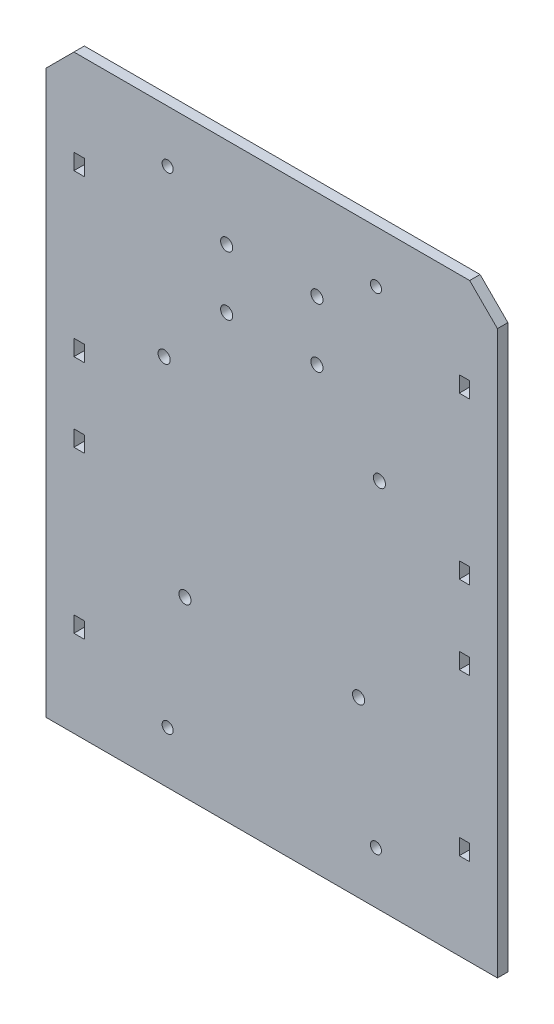
SolidWorks part; units mm, degrees
ref_plane "正面" through (0, 0, 0) normal (0, 0, 1) x (1, 0, 0)
ref_plane "平面" through (0, 0, 0) normal (0, 1, 0) x (1, 0, 0)
ref_plane "右側面" through (0, 0, 0) normal (1, 0, 0) x (0, 0, -1)
sketch "ｽｹｯﾁ1" plane through (0, 0, 0) normal (0, 0, 1) x (1, 0, 0)
  line L0 (0, 162) -> (8, 170)
  line L1 (0, 0) -> (130, 0)
  line L2 (0, 0) -> (0, 162)
  line L3 (8, 170) -> (122, 170)
  line L4 (130, 0) -> (130, 162)
  line L5 (8, 145) -> (11, 145)
  line L6 (8, 145) -> (8, 140.4)
  line L7 (8, 140.4) -> (11, 140.4)
  line L8 (11, 145) -> (11, 140.4)
  line L9 (122, 145) -> (119, 145)
  line L10 (122, 145) -> (122, 140.4)
  line L11 (122, 140.4) -> (119, 140.4)
  line L12 (119, 145) -> (119, 140.4)
  line L13 (8, 29.6) -> (11, 29.6)
  line L14 (8, 29.6) -> (8, 25)
  line L15 (8, 25) -> (11, 25)
  line L16 (11, 29.6) -> (11, 25)
  line L17 (119, 29.6) -> (122, 29.6)
  line L18 (119, 29.6) -> (119, 25)
  line L19 (119, 25) -> (122, 25)
  line L20 (122, 29.6) -> (122, 25)
  line L21 (8, 98.6) -> (11, 98.6)
  line L22 (8, 98.6) -> (8, 94)
  line L23 (8, 94) -> (11, 94)
  line L24 (11, 98.6) -> (11, 94)
  line L25 (119, 98.6) -> (122, 98.6)
  line L26 (119, 98.6) -> (119, 94)
  line L27 (119, 94) -> (122, 94)
  line L28 (122, 98.6) -> (122, 94)
  line L29 (8, 76) -> (11, 76)
  line L30 (8, 76) -> (8, 71.4)
  line L31 (8, 71.4) -> (11, 71.4)
  line L32 (11, 76) -> (11, 71.4)
  line L33 (119, 76) -> (122, 76)
  line L34 (119, 76) -> (119, 71.4)
  line L35 (119, 71.4) -> (122, 71.4)
  line L36 (122, 76) -> (122, 71.4)
  line L37 (122, 170) -> (130, 162)
  circle A0 centre (35, 155) radius 1.6
  circle A1 centre (95, 155) radius 1.6
  circle A2 centre (35, 15) radius 1.6
  circle A3 centre (95, 15) radius 1.6
  circle A4 centre (34, 107) radius 1.75
  circle A5 centre (96, 107) radius 1.75
  circle A6 centre (40, 50) radius 1.75
  circle A7 centre (90, 50) radius 1.75
  circle A8 centre (52, 144) radius 1.75
  circle A9 centre (78, 144) radius 1.75
  circle A10 centre (52, 127) radius 1.75
  circle A11 centre (78, 127) radius 1.75
  point P21 (119, 142.7)
  point P38 (8, 27.3)
  point P39 (9.5, 25)
  point P66 (0, 0)
  dimension "D40" = 3.2
  dimension "D41" = 3.2
  dimension "D42" = 3.2
  dimension "D43" = 3.2
  dimension "D52" = 3.5
  dimension "D53" = 3.5
  dimension "D54" = 3.5
  dimension "D55" = 3.5
  dimension "D64" = 3.5
  dimension "D65" = 3.5
  dimension "D66" = 3.5
  dimension "D67" = 3.5
  dimension "D1" = 170
  dimension "D3" = 3
  dimension "D4" = 4.6
  dimension "D5" = 3
  dimension "D6" = 4.6
  dimension "D7" = 3
  dimension "D8" = 4.6
  dimension "D9" = 3
  dimension "D10" = 4.6
  dimension "D11" = 3
  dimension "D12" = 4.6
  dimension "D13" = 3
  dimension "D14" = 4.6
  dimension "D15" = 4.6
  dimension "D16" = 3
  dimension "D17" = 3
  dimension "D18" = 4.6
  dimension "D19" = 51
  dimension "D20" = 51
  dimension "D21" = 8
  dimension "D22" = 8
  dimension "D23" = 8
  dimension "D24" = 8
  dimension "D25" = 8
  dimension "D26" = 8
  dimension "D27" = 51
  dimension "D28" = 51
  dimension "D29" = 8
  dimension "D30" = 8
  dimension "D31" = 25
  dimension "D32" = 25
  dimension "D33" = 25
  dimension "D34" = 25
  dimension "D35" = 130
  dimension "D36" = 8
  dimension "D37" = 11.3137
  dimension "D38" = 11.3137
  dimension "D39" = 45
  dimension "D44" = 35
  dimension "D45" = 35
  dimension "D46" = 35
  dimension "D47" = 35
  dimension "D48" = 140
  dimension "D49" = 140
  dimension "D50" = 15
  dimension "D51" = 15
  dimension "D56" = 62
  dimension "D57" = 50
  dimension "D58" = 34
  dimension "D59" = 40
  dimension "D60" = 63
  dimension "D61" = 57
  dimension "D62" = 17
  dimension "D63" = 26
  dimension "D68" = 20
  dimension "D69" = 52
extrude "ﾎﾞｽ - 押し出し1" add sketch "ｽｹｯﾁ1" along normal blind 3
